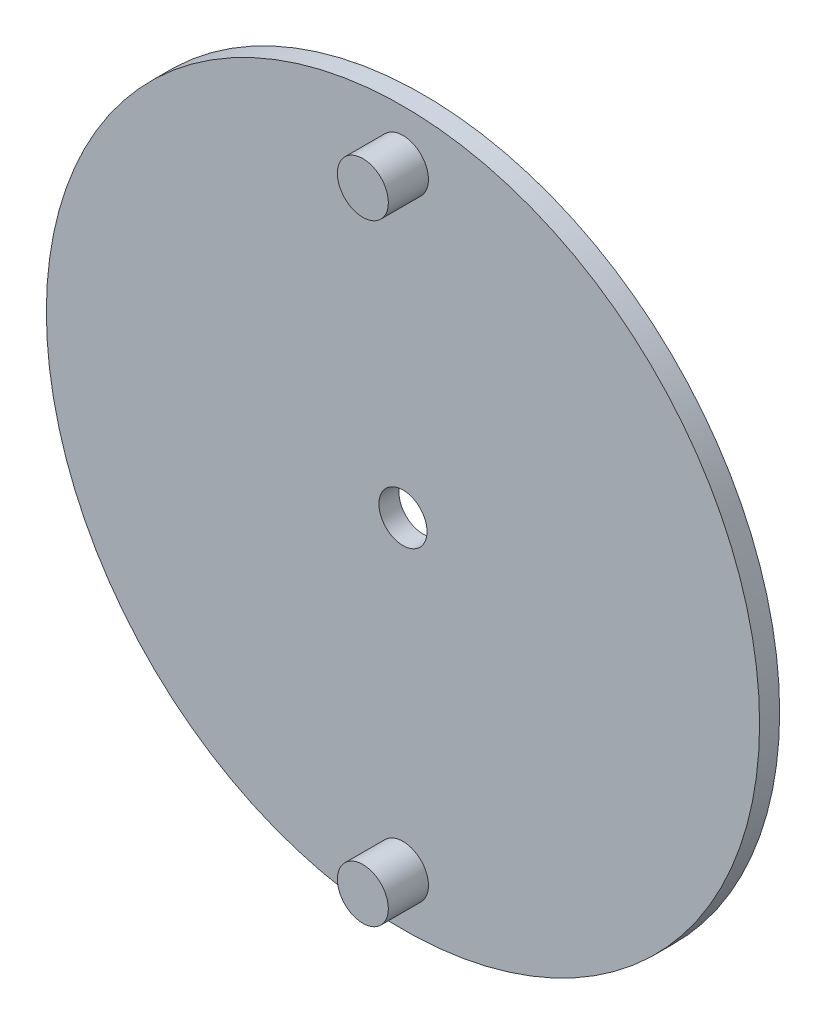
SolidWorks part; units mm, degrees
ref_plane "Front Plane" through (0, 0, 0) normal (0, 0, 1) x (1, 0, 0)
ref_plane "Top Plane" through (0, 0, 0) normal (0, 1, 0) x (1, 0, 0)
ref_plane "Right Plane" through (0, 0, 0) normal (1, 0, 0) x (0, 0, -1)
sketch "Sketch1" plane through (0, 0, 0) normal (0, 0, 1) x (1, 0, 0)
  line L0 (-169.7289, -88.9) -> (169.7289, -88.9) construction
  line L1 (-110.0162, 88.9) -> (110.0162, 88.9) construction
  circle A0 centre (0, 0) radius 88.9
  circle A1 centre (0, 0) radius 6
  circle A2 centre (0, -76.2) radius 6.35
  circle A3 centre (0, 76.2) radius 6.35
  point P7 (0, -88.9)
  point P14 (0, 88.9)
  point P15 (110.0162, 75.6194)
  dimension "D1" = 177.8
  dimension "D2" = 12.7
  dimension "D3" = 12
  dimension "D5" = 12.7
  dimension "D4" = 12.7
  dimension "D6" = 12.7
extrude "Boss-Extrude1" add sketch "Sketch1" along normal blind 5
sketch "Sketch2" plane through (0, 0, 0) normal (0, 0, 1) x (1, 0, 0)
  circle A0 centre (0, -76.2) radius 6.35
  circle A1 centre (0, 76.2) radius 6.35
  circle A3 centre (0, 76.2) radius 6.35 construction
extrude "Boss-Extrude2" add sketch "Sketch2" along normal blind 15
